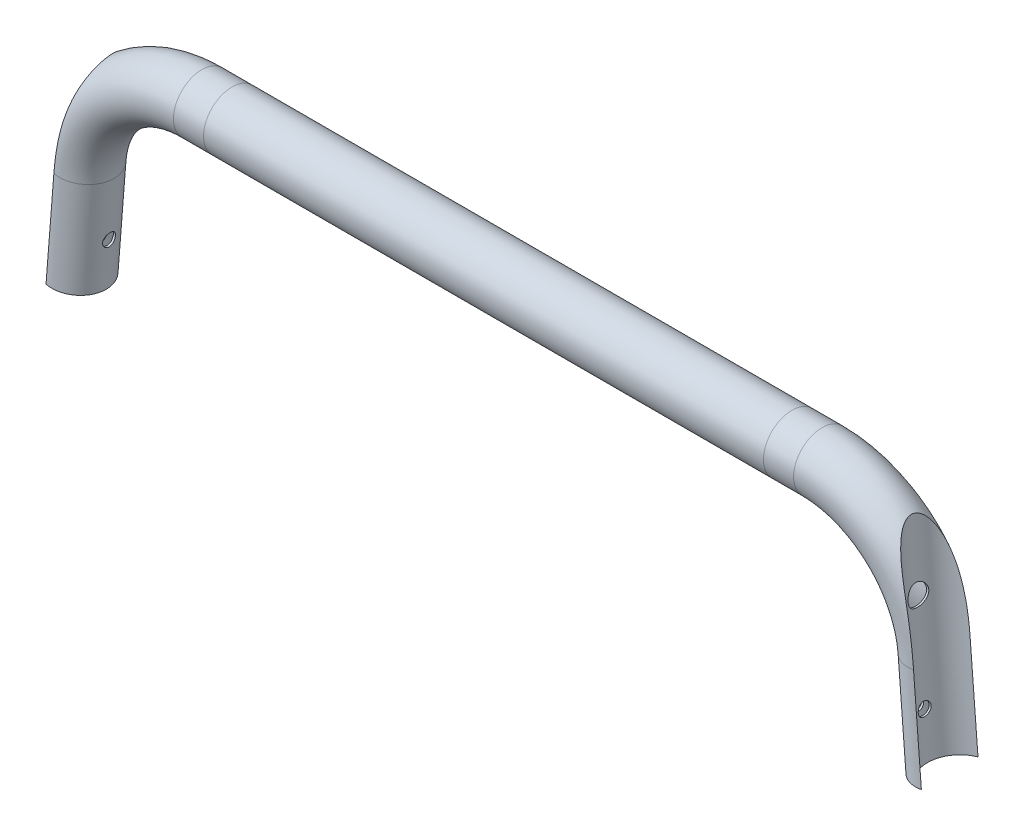
SolidWorks part; units mm, degrees
ref_plane "Front Plane" through (0, 0, 0) normal (0, 0, 1) x (1, 0, 0)
ref_plane "Top Plane" through (0, 0, 0) normal (0, 1, 0) x (1, 0, 0)
ref_plane "Right Plane" through (0, 0, 0) normal (1, 0, 0) x (0, 0, -1)
sketch "Sketch1" plane through (0, 0, 0) normal (0, 0, 1) x (1, 0, 0)
  line L0 (-108, 0) -> (108, 0)
  line L1 (0, 0) -> (0, -80) construction
  line L3 (-167.5, -80) -> (-164.4676, -41.4693)
  line L4 (-119.6063, 0) -> (-108, 0)
  line L5 (167.5, -80) -> (164.4676, -41.4693)
  line L6 (119.6063, 0) -> (108, 0)
  arc A0 (164.4676, -41.4693) -> (119.6063, 0) centre (119.6063, -45) ccw
  arc A1 (-119.6063, 0) -> (-164.4676, -41.4693) centre (-119.6063, -45) ccw
  point P4 (0, 0)
  point P11 (0, -80)
  dimension "D5" = 45
  dimension "D1" = 216
  dimension "D2" = 80
  dimension "D3" = 94.5
  dimension "D4" = 94.5
  dimension "D6" = 80
  dimension "D7" = 335
ref_plane "Plane1" through (-167.5, -80, 0) normal (-0.0785, -0.9969, 0) x (-0.9969, 0.0785, 0)
sketch "Sketch2" plane through (-167.5, -80, 0) normal (-0.0785, -0.9969, 0) x (-0.9969, 0.0785, 0)
  line L0 (-41.4693, 0) -> (0, 0) construction
  circle A0 centre (0, 0) radius 11
  circle A1 centre (0, 0) radius 10.2
  dimension "D1" = 0.8
sweep "Sweep1" add profiles "Sketch2" path "Sketch1"
sketch "Sketch3" plane through (7.2885, -92.6089, 0) normal (0.0785, -0.9969, 0) x (0.9969, 0.0785, 0)
  line L0 (160.7069, 0) -> (164.7069, 0) construction
  circle A0 centre (164.7069, 0) radius 11.2358
  dimension "D1" = 4
extrude "Cut-Extrude1" cut sketch "Sketch3" against normal through all
mirror "Mirror1" about plane through (0, 0, 0) normal (1, 0, 0) of "Cut-Extrude1"
sketch "Sketch6" plane through (7.2885, -92.6089, 0) normal (0.0785, -0.9969, 0) x (0.9969, 0.0785, 0)
  line L0 (160.7069, 0) -> (164.7069, 0) construction
  arc A0 (162.0515, 10.9175) -> (162.0515, -10.9175) centre (164.7069, 0) ccw
  arc A2 (159.7243, 10.956) -> (159.7243, -10.956) centre (164.7069, 0) ccw
  arc A3 (159.7243, -10.956) -> (162.0515, -10.9175) centre (160.7069, 0) ccw
  circle A4 centre (164.7069, 0) radius 12.0358 construction
  circle A5 centre (164.7069, 0) radius 11.2358 construction
  arc A6 (162.0515, 10.9175) -> (159.7243, 10.956) centre (160.7069, 0) ccw
  dimension "D1" = 0.8
extrude "Boss-Extrude1" add sketch "Sketch6" against normal up to next
mirror "Mirror2" about plane through (0, 0, 0) normal (1, 0, 0) of "Boss-Extrude1"
sketch "Sketch7" plane through (7.2885, -92.6089, 0) normal (0.0785, -0.9969, 0) x (0.9969, 0.0785, 0)
  line L0 (149.7069, 0) -> (160.7069, 0)
  arc A0 (162.0515, 10.9175) -> (162.0515, -10.9175) centre (160.7069, 0) ccw construction
ref_plane "Plane2" through (167.5, -80, 0) normal (0.9969, 0.0785, 0) x (0, 0, -1)
sketch "Sketch8" plane through (167.5, -80, 0) normal (0.9969, 0.0785, 0) x (0, 0, -1)
  line L0 (0, 0.0022) -> (0, 17.3022) construction
  circle A0 centre (0, 17.3022) radius 2.5
  dimension "D1" = 17.3
extrude "Cut-Extrude2" cut sketch "Sketch8" against normal up to surface (323.8568 mm away)
mirror "Mirror3" about plane through (0, 0, 0) normal (1, 0, 0) of "Cut-Extrude2"
sketch "Sketch9" plane through (167.5, -80, 0) normal (0.9969, 0.0785, 0) x (0, 0, -1)
  line L0 (0, 0) -> (0, 54.0645) construction
  line L1 (-10.9175, 0) -> (10.9175, 0) construction
  circle A0 centre (0, 54.0645) radius 4
extrude "Cut-Extrude3" cut sketch "Sketch9" against normal up to next
